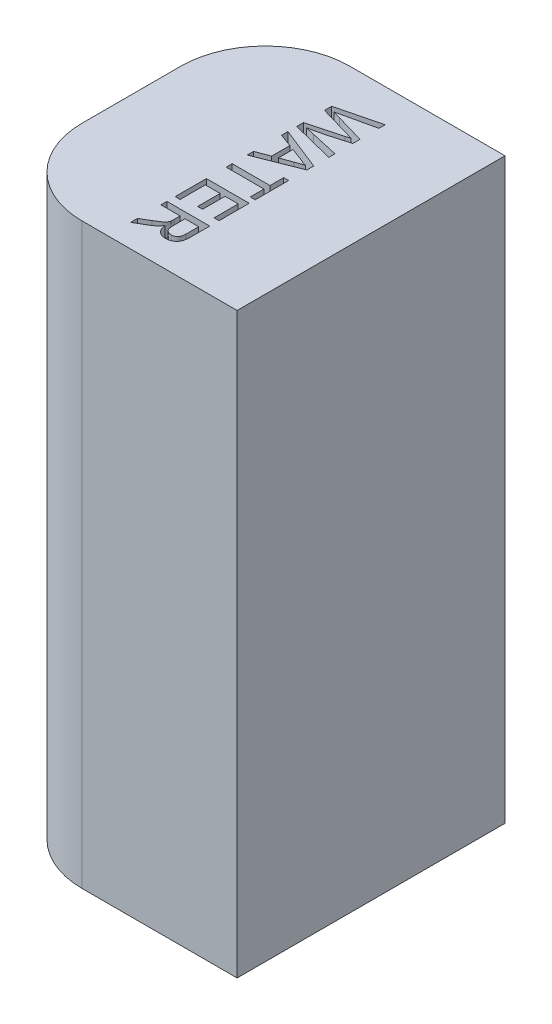
SolidWorks part; units mm, degrees
ref_plane "Front" through (0, 0, 0) normal (0, 0, 1) x (1, 0, 0)
ref_plane "Top" through (0, 0, 0) normal (0, 1, 0) x (1, 0, 0)
ref_plane "Right" through (0, 0, 0) normal (1, 0, 0) x (0, 0, -1)
sketch "Sketch1" plane through (0, 0, 0) normal (0, 1, 0) x (1, 0, 0)
  line L1 (-215.9, 241.3) -> (215.9, 241.3)
  line L2 (-215.9, 241.3) -> (-215.9, -241.3)
  line L3 (-215.9, -241.3) -> (215.9, -241.3)
  line L4 (215.9, 241.3) -> (215.9, -241.3)
  line L5 (-215.9, 241.3) -> (215.9, -241.3) construction
  line L6 (-215.9, -241.3) -> (215.9, 241.3) construction
  point P0 (0, 0)
  dimension "D1" = 431.8
  dimension "D2" = 482.6
extrude "Boss-Extrude1" add sketch "Sketch1" along normal blind 1041.4
fillet "Fillet1" radius 152.4 2 edges at (-215.9, 520.7, -241.3) (-215.9, 520.7, 241.3)
sketch "Sketch2" plane through (0, 1041.4, 0) normal (0, 1, 0) x (1, 0, 0)
  line L0 (-17.4864, 182.7581) -> (-17.4864, -191.084) construction
  text T0 "WATER" font "Arial" height in points 300
extrude "Cut-Extrude1" cut sketch "Sketch2" against normal blind 25.4
